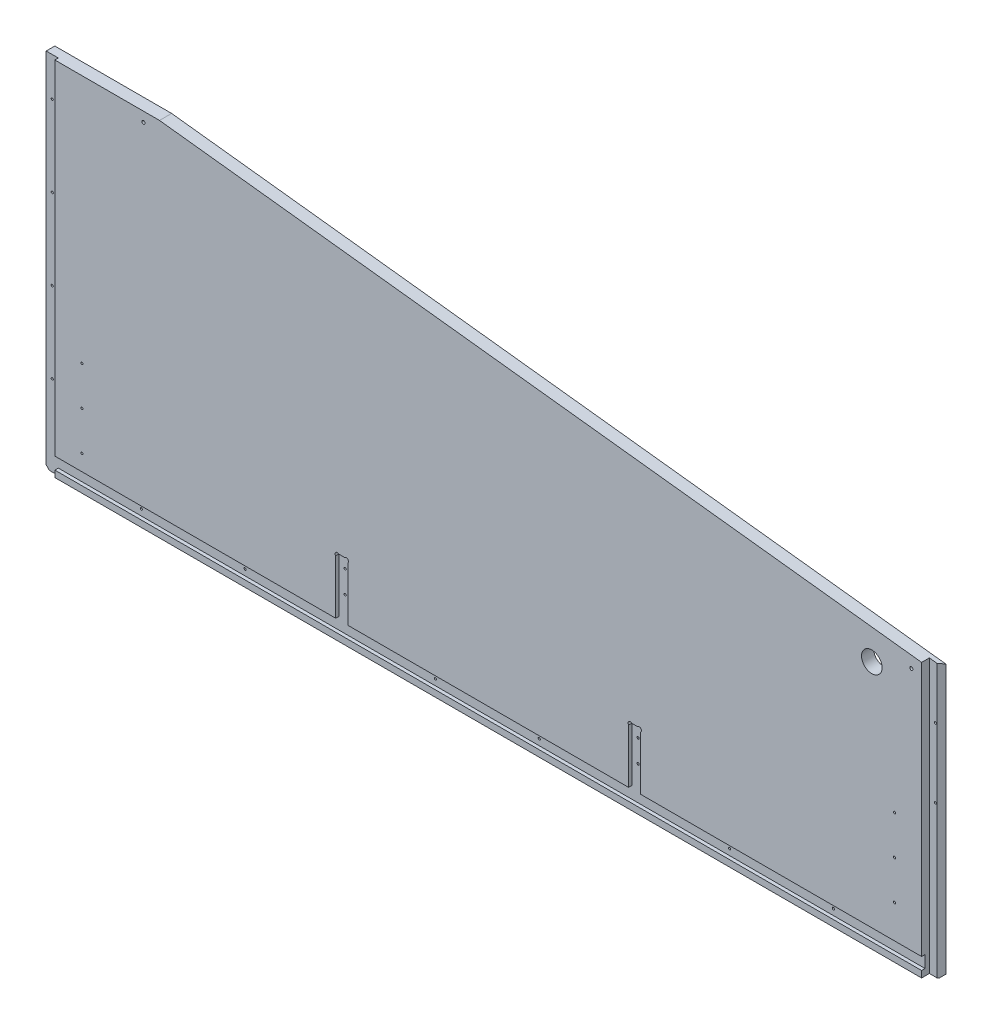
SolidWorks part; units mm, degrees
material "Pine"
ref_plane "Front Plane" through (0, 0, 0) normal (0, 0, 1) x (1, 0, 0)
ref_plane "Top Plane" through (0, 0, 0) normal (0, 1, 0) x (1, 0, 0)
ref_plane "Right Plane" through (0, 0, 0) normal (1, 0, 0) x (0, 0, -1)
sketch "Sketch1" plane through (0, 0, 0) normal (0, 0, 1) x (1, 0, 0)
  line L0 (8932.6508, -5243.5125) -> (10226.1458, -5243.5125)
  line L1 (9086.3208, -4722.0918) -> (10222.9708, -4853.7812)
  line L2 (8914.8708, -6342.0625) -> (10197.5708, -6342.0625)
  line L3 (8914.8708, -5808.6625) -> (10197.5708, -5808.6625)
  line L4 (8919.6333, -5253.0375) -> (10218.2083, -5253.0375)
  line L5 (9134.2633, -4656.1375) -> (9134.2633, -4638.3575)
  line L6 (9091.0833, -4638.3575) -> (9134.2633, -4638.3575)
  line L7 (9091.0833, -4567.2375) -> (9091.0833, -4638.3575)
  line L8 (9134.2633, -4656.1375) -> (9581.3033, -4656.1375)
  line L9 (9091.0833, -4567.2375) -> (9624.4833, -4567.2375)
  line L10 (9581.3033, -4656.1375) -> (9581.3033, -4638.3575)
  line L11 (9581.3033, -4638.3575) -> (9624.4833, -4638.3575)
  line L12 (9624.4833, -4567.2375) -> (9624.4833, -4638.3575)
  line L13 (8932.6508, -5225.7325) -> (9344.9775, -5225.7325)
  line L14 (8932.6508, -5256.2125) -> (8932.6508, -5243.5125)
  line L15 (8911.6958, -5256.2125) -> (8932.6508, -5256.2125)
  line L16 (8914.8708, -4722.0918) -> (9086.3208, -4722.0918)
  line L17 (8911.6958, -4715.5913) -> (8932.6508, -4715.5913)
  line L18 (8914.8708, -6342.0625) -> (8914.8708, -5808.6625)
  line L19 (12082.9917, -4722.0918) -> (10946.3417, -4853.7812)
  line L20 (12236.6617, -5243.5125) -> (10943.1667, -5243.5125)
  line L21 (10951.1042, -5253.0375) -> (12249.6792, -5253.0375)
  line L22 (10838.3917, -5656.2625) -> (11308.2917, -5656.2625)
  line L23 (10838.3917, -5719.7625) -> (11308.2917, -5719.7625)
  line L24 (10838.3917, -5742.5368) -> (11308.2917, -5742.5368)
  line L25 (10806.6417, -6342.0625) -> (11340.0417, -6342.0625)
  line L26 (10803.4667, -6335.7125) -> (11343.2167, -6335.7125)
  line L27 (10803.4667, -6317.9325) -> (11343.2167, -6317.9325)
  line L28 (10943.1667, -5225.7325) -> (11376.4483, -5225.7325)
  line L29 (11506.7292, -4754.5625) -> (10806.6417, -4827.5875)
  line L30 (11506.7292, -4567.2375) -> (11506.7292, -4754.5625)
  line L31 (10806.6417, -4567.2375) -> (10806.6417, -4827.5875)
  line L32 (10806.6417, -4567.2375) -> (11506.7292, -4567.2375)
  line L33 (10235.6708, -6329.3625) -> (10245.1958, -6329.3625)
  line L34 (10245.1958, -6329.3625) -> (10254.7208, -6278.5625)
  line L35 (10302.3458, -6329.3625) -> (10311.8708, -6278.5625)
  line L36 (10302.3458, -6329.3625) -> (10292.8208, -6329.3625)
  line L37 (10245.1958, -5821.3625) -> (10254.7208, -5872.1625)
  line L38 (10235.6708, -5821.3625) -> (10245.1958, -5821.3625)
  line L39 (10292.8208, -5821.3625) -> (10302.3458, -5821.3625)
  line L40 (10302.3458, -5821.3625) -> (10311.8708, -5872.1625)
  line L41 (10235.6708, -5821.3625) -> (10235.6708, -6329.3625)
  line L42 (10254.7208, -5872.1625) -> (10254.7208, -6278.5625)
  line L43 (10311.8708, -5872.1625) -> (10311.8708, -6278.5625)
  line L44 (10292.8208, -5821.3625) -> (10292.8208, -6329.3625)
  line L45 (8932.6508, -5225.7325) -> (8932.6508, -4715.5913)
  line L46 (8911.6958, -4715.5913) -> (8911.6958, -5256.2125)
  line L47 (8914.8708, -5248.275) -> (8914.8708, -4722.0918)
  line L48 (8919.6333, -5253.0375) -> (8914.8708, -5248.275)
  line L49 (8914.8708, -5145.0875) -> (8937.426, -5145.0875)
  line L50 (8914.8708, -5202.2375) -> (8937.426, -5202.2375)
  line L51 (10838.3917, -5656.2625) -> (10838.3917, -5719.7625)
  line L52 (10832.0417, -5736.1868) -> (10856.1717, -5736.1868)
  line L53 (10806.6417, -6342.0625) -> (10806.6417, -5818.7368)
  line L54 (10832.0417, -5649.9125) -> (10856.1717, -5649.9125)
  line L55 (10832.0417, -5726.1125) -> (10856.1717, -5726.1125)
  line L56 (10806.6417, -5818.7368) -> (10833.9015, -5818.7368)
  line L57 (10832.0417, -5806.0442) -> (10851.6815, -5806.0442)
  line L58 (10856.1717, -5801.5541) -> (10856.1717, -5736.1868)
  line L59 (10838.3917, -5814.2467) -> (10838.3917, -5742.5368)
  line L60 (10832.0417, -5806.0442) -> (10832.0417, -5736.1868)
  line L61 (10803.4667, -6317.9325) -> (10803.4667, -6335.7125)
  line L62 (10197.5708, -5808.6625) -> (10197.5708, -6342.0625)
  line L63 (9762.3842, -6348.4125) -> (9762.3842, -5802.3125)
  line L64 (9780.1642, -6348.4125) -> (9762.3842, -6348.4125)
  line L65 (9780.1642, -5802.3125) -> (9780.1642, -6348.4125)
  line L66 (9762.3842, -5802.3125) -> (9780.1642, -5802.3125)
  line L67 (9332.2775, -6348.4125) -> (9332.2775, -5802.3125)
  line L68 (9332.2775, -6348.4125) -> (9350.0575, -6348.4125)
  line L69 (9350.0575, -5802.3125) -> (9350.0575, -6348.4125)
  line L70 (9332.2775, -5802.3125) -> (9350.0575, -5802.3125)
  line L71 (9993.8374, -6061.075) -> (9993.8374, -6045.2418)
  line L72 (9998.5999, -6065.8375) -> (10014.4331, -6065.8375)
  line L73 (9998.5999, -6084.8875) -> (10014.4331, -6084.8875)
  line L74 (9993.8374, -6105.4832) -> (9993.8374, -6089.65)
  line L75 (9974.7874, -6105.4832) -> (9974.7874, -6089.65)
  line L76 (9954.1917, -6084.8875) -> (9970.0249, -6084.8875)
  line L77 (9974.7874, -6061.075) -> (9974.7874, -6045.2418)
  line L78 (9954.1917, -6065.8375) -> (9970.0249, -6065.8375)
  line L79 (10793.9417, -6237.2875) -> (10816.4969, -6237.2875)
  line L80 (10793.9417, -6294.4375) -> (10816.4969, -6294.4375)
  line L81 (10856.1717, -5649.9125) -> (10856.1717, -5726.1125)
  line L82 (10832.0417, -5726.1125) -> (10832.0417, -5649.9125)
  line L83 (10226.1458, -5225.7325) -> (10226.1458, -5243.5125)
  line L84 (10205.1908, -5257.8) -> (10205.1908, -4844.2499)
  line L85 (10230.9083, -4844.2499) -> (10230.9083, -5257.8)
  line L86 (10205.1908, -5257.8) -> (10230.9083, -5257.8)
  line L87 (10205.1908, -4844.2499) -> (10230.9083, -4844.2499)
  line L88 (10946.3417, -5176.8375) -> (10968.8969, -5176.8375)
  line L89 (9349.4676, -5141.9125) -> (9358.2674, -5141.9125)
  line L90 (10946.3417, -5119.6875) -> (10968.8969, -5119.6875)
  line L91 (9929.011, -4660.9635) -> (10066.0807, -4660.9635)
  line L92 (9929.011, -4678.7435) -> (10066.0807, -4678.7435)
  line L93 (10943.1667, -5225.7325) -> (10943.1667, -5243.5125)
  line L94 (10946.3417, -5248.275) -> (10951.1042, -5253.0375)
  line L95 (10946.3417, -5257.8063) -> (10946.3417, -4849.0188)
  line L96 (10964.1217, -5257.8) -> (10964.1217, -4844.2499)
  line L97 (10938.4042, -4844.2499) -> (10938.4042, -5257.8)
  line L98 (10938.4042, -5257.8) -> (10964.1217, -5257.8)
  line L99 (10964.1217, -4844.2499) -> (10938.4042, -4844.2499)
  line L100 (10344.8908, -4560.8875) -> (10369.0208, -4560.8875)
  line L101 (10344.8908, -4560.8875) -> (10369.0208, -4560.8875)
  line L102 (10800.2917, -4560.8875) -> (10824.4217, -4560.8875)
  line L103 (10200.4156, -5119.6875) -> (10222.9708, -5119.6875)
  line L104 (10200.4156, -5176.8375) -> (10222.9708, -5176.8375)
  line L105 (9344.9775, -5146.4026) -> (9344.9775, -5225.7325)
  line L106 (10344.8908, -4560.8875) -> (10344.8908, -4833.9375)
  line L107 (9792.8642, -5225.7325) -> (9792.8642, -5146.4026)
  line L108 (9362.7575, -5225.7325) -> (9775.0842, -5225.7325)
  line L109 (9680.3633, -4761.8396) -> (9680.3633, -4559.9604)
  line L110 (9656.2333, -4559.9604) -> (9680.3633, -4559.9604)
  line L111 (9656.2333, -4761.8396) -> (9680.3633, -4761.8396)
  line L112 (9656.2333, -4761.8396) -> (9656.2333, -4559.9604)
  line L113 (9779.5743, -5141.9125) -> (9788.374, -5141.9125)
  line L114 (10070.5708, -4665.4536) -> (10070.5708, -4674.2534)
  line L115 (9924.5208, -4674.2534) -> (9924.5208, -4665.4536)
  line L116 (12127.4417, -6188.3925) -> (12205.5015, -6188.3925)
  line L117 (12209.9917, -6170.6125) -> (12209.9917, -6183.9024)
  line L118 (9792.8642, -5225.7325) -> (10226.1458, -5225.7325)
  line L119 (9662.5833, -4754.5625) -> (10362.6708, -4827.5875)
  line L120 (9662.5833, -4567.2375) -> (9662.5833, -4754.5625)
  line L121 (10362.6708, -4567.2375) -> (10362.6708, -4827.5875)
  line L122 (9662.5833, -4567.2375) -> (10362.6708, -4567.2375)
  line L123 (10824.4217, -4833.9375) -> (10800.2917, -4833.9375)
  line L124 (10800.2917, -4833.9375) -> (10800.2917, -4560.8875)
  line L125 (10824.4217, -4560.8875) -> (10824.4217, -4833.9375)
  line L126 (10344.8908, -4833.9375) -> (10369.0208, -4833.9375)
  line L127 (10369.0208, -4833.9375) -> (10369.0208, -4560.8875)
  line L128 (10222.9708, -5248.275) -> (10218.2083, -5253.0375)
  line L129 (10222.9708, -5257.8063) -> (10222.9708, -4849.0188)
  line L130 (11734.6544, -5701.375) -> (11739.2301, -5701.375)
  line L131 (9362.7575, -5225.7325) -> (9362.7575, -5146.4026)
  line L132 (9775.0842, -5146.4026) -> (9775.0842, -5225.7325)
  line L133 (11761.3864, -5701.375) -> (11756.8282, -5701.375)
  line L134 (11734.6544, -5693.755) -> (11739.2301, -5693.755)
  line L135 (11761.4039, -5693.755) -> (11756.8282, -5693.755)
  line L136 (11734.6544, -5701.375) -> (11739.2301, -5701.375)
  line L137 (11744.3462, -5721.3024) -> (11744.3462, -5706.4179)
  line L138 (11751.7122, -5721.3024) -> (11751.7122, -5706.4179)
  line L139 (11740.0917, -6170.6125) -> (11740.0917, -6183.9024)
  line L140 (11689.2917, -6188.3925) -> (11822.6417, -6188.3925)
  line L141 (11689.2917, -6348.4093) -> (11689.2917, -6164.2657)
  line L142 (11689.2917, -6164.2657) -> (11746.4417, -6164.2657)
  line L143 (11746.4417, -6164.2657) -> (11746.4417, -6188.3925)
  line L144 (11689.2917, -6164.2657) -> (11746.4417, -6164.2657)
  line L145 (11340.0417, -5818.7368) -> (11340.0417, -6342.0625)
  line L146 (11290.5117, -5726.1125) -> (11314.6417, -5726.1125)
  line L147 (11290.5117, -5649.9125) -> (11290.5117, -5726.1125)
  line L148 (11340.0417, -5818.7368) -> (11312.7818, -5818.7368)
  line L149 (11314.6417, -5806.0442) -> (11295.0018, -5806.0442)
  line L150 (11290.5117, -5801.5541) -> (11290.5117, -5736.1868)
  line L151 (11308.2917, -5814.2467) -> (11308.2917, -5742.5368)
  line L152 (11314.6417, -5806.0442) -> (11314.6417, -5736.1868)
  line L153 (11290.5117, -5736.1868) -> (11314.6417, -5736.1868)
  line L154 (11848.0417, -6267.1325) -> (11962.3417, -6267.1325)
  line L155 (11962.3417, -6267.1325) -> (11962.3417, -6203.6325)
  line L156 (11343.2167, -6317.9325) -> (11343.2167, -6335.7125)
  line L157 (11365.4417, -5656.2625) -> (11365.4417, -5719.7625)
  line L158 (11365.4417, -5656.2625) -> (11479.7417, -5656.2625)
  line L159 (11778.1917, -6071.3937) -> (11802.3217, -6071.3937)
  line L160 (11314.6417, -5726.1125) -> (11314.6417, -5649.9125)
  line L161 (11314.6417, -5649.9125) -> (11290.5117, -5649.9125)
  line L162 (11308.2917, -5719.7625) -> (11308.2917, -5656.2625)
  line L163 (11689.2917, -6348.4093) -> (11713.4217, -6348.4093)
  line L164 (12203.6417, -6164.2657) -> (12260.7917, -6164.2657)
  line L165 (11713.4217, -6348.4093) -> (11713.4217, -6164.2657)
  line L166 (11695.6417, -6342.0625) -> (11695.6417, -6170.6125)
  line L167 (11695.6417, -6048.5337) -> (11699.4517, -6052.3437)
  line L168 (11822.6417, -6292.5325) -> (11822.6417, -6188.3925)
  line L169 (11695.6417, -6342.0625) -> (11695.6417, -6170.6125)
  line L170 (11848.0417, -6203.6325) -> (11962.3417, -6203.6325)
  line L171 (11848.0417, -6203.6325) -> (11848.0417, -6267.1325)
  line L172 (11987.7417, -6267.1325) -> (11987.7417, -6203.6325)
  line L173 (11784.5417, -6077.7437) -> (11784.5417, -6141.2438)
  line L174 (11517.8417, -5656.2625) -> (11632.1417, -5656.2625)
  line L175 (11632.1417, -5656.2625) -> (11632.1417, -5719.7625)
  line L176 (11632.1417, -5719.7625) -> (11517.8417, -5719.7625)
  line L177 (11517.8417, -5719.7625) -> (11517.8417, -5656.2625)
  line L178 (11692.4667, -6028.2137) -> (11692.4667, -6045.9937)
  line L179 (11695.6417, -5979.3188) -> (11718.1969, -5979.3188)
  line L180 (11695.6417, -5922.1687) -> (11718.1969, -5922.1687)
  line L181 (11821.0415, -5722.9375) -> (11821.0415, -5943.6)
  line L182 (11687.7042, -5651.5) -> (11701.9917, -5651.5)
  line L183 (11687.7042, -5651.5) -> (11687.7042, -6055.5251)
  line L184 (11687.7042, -6055.5251) -> (11701.9917, -6055.5251)
  line L185 (11701.9917, -6055.5251) -> (11701.9917, -5651.5)
  line L186 (11695.6417, -6055.2013) -> (11695.6417, -5649.595)
  line L187 (11695.6417, -5656.2625) -> (11695.6417, -6048.5337)
  line L188 (11695.6417, -6170.6125) -> (11740.0917, -6170.6125)
  line L189 (12203.6417, -6164.2657) -> (12203.6417, -6188.3925)
  line L190 (12254.4417, -6342.0625) -> (12254.4417, -6170.6125)
  line L191 (12129.0419, -5943.6) -> (12129.0419, -5722.9375)
  line L192 (12254.4417, -6048.5337) -> (12250.6317, -6052.3437)
  line L193 (12257.6167, -6045.9937) -> (12257.6167, -6028.2137)
  line L194 (12248.0917, -5651.5) -> (12262.3792, -5651.5)
  line L195 (12262.3792, -5651.5) -> (12262.3792, -6055.5251)
  line L196 (12262.3792, -6055.5251) -> (12248.0917, -6055.5251)
  line L197 (12248.0917, -6055.5251) -> (12248.0917, -5651.5)
  line L198 (12254.4417, -6141.2438) -> (12254.4417, -6077.7437)
  line L199 (12236.6617, -6164.2657) -> (12260.7917, -6164.2657)
  line L200 (12102.0417, -6267.1325) -> (11987.7417, -6267.1325)
  line L201 (11330.1865, -6237.2875) -> (11352.7417, -6237.2875)
  line L202 (11330.1865, -6294.4375) -> (11352.7417, -6294.4375)
  line L203 (11474.6617, -5851.8425) -> (11492.4417, -5851.8425)
  line L204 (11474.6617, -5808.6625) -> (11474.6617, -5851.8425)
  line L205 (11403.5417, -5808.6625) -> (11474.6617, -5808.6625)
  line L206 (11492.4417, -5851.8425) -> (11492.4417, -6298.8825)
  line L207 (11403.5417, -6342.0625) -> (11403.5417, -5808.6625)
  line L208 (11474.6617, -6298.8825) -> (11492.4417, -6298.8825)
  line L209 (11474.6617, -6342.0625) -> (11474.6617, -6298.8825)
  line L210 (11403.5417, -6342.0625) -> (11474.6617, -6342.0625)
  line L211 (11619.4417, -5851.8425) -> (11601.6617, -5851.8425)
  line L212 (11601.6617, -5808.6625) -> (11601.6617, -5851.8425)
  line L213 (11530.5417, -5808.6625) -> (11601.6617, -5808.6625)
  line L214 (11619.4417, -5851.8425) -> (11619.4417, -6298.8825)
  line L215 (11530.5417, -6342.0625) -> (11530.5417, -5808.6625)
  line L216 (11619.4417, -6298.8825) -> (11601.6617, -6298.8825)
  line L217 (11601.6617, -6342.0625) -> (11601.6617, -6298.8825)
  line L218 (11530.5417, -6342.0625) -> (11601.6617, -6342.0625)
  line L219 (11479.7417, -5719.7625) -> (11479.7417, -5656.2625)
  line L220 (11365.4417, -5719.7625) -> (11479.7417, -5719.7625)
  line L221 (11778.1917, -6147.5937) -> (11802.3217, -6147.5937)
  line L222 (11802.3217, -6071.3937) -> (11802.3217, -6147.5937)
  line L223 (11778.1917, -6147.5937) -> (11778.1917, -6071.3937)
  line L224 (12254.4417, -5922.1687) -> (12231.8865, -5922.1687)
  line L225 (12254.4417, -5979.3188) -> (12231.8865, -5979.3188)
  line L226 (12254.4417, -6055.2013) -> (12254.4417, -5649.595)
  line L227 (12254.4417, -6048.5337) -> (12254.4417, -5656.2625)
  line L228 (11841.6917, -5702.2873) -> (12108.3917, -5702.2873)
  line L229 (11822.6417, -6292.5325) -> (12127.4417, -6292.5325)
  line L230 (12127.4417, -6292.5325) -> (12127.4417, -6188.3925)
  line L231 (12254.4417, -6170.6125) -> (12209.9917, -6170.6125)
  line L232 (11695.6417, -6342.0625) -> (12254.4417, -6342.0625)
  line L233 (12236.6617, -6348.4093) -> (12260.7917, -6348.4093)
  line L234 (12260.7917, -6348.4093) -> (12260.7917, -6164.2657)
  line L235 (12236.6617, -6348.4093) -> (12236.6617, -6164.2657)
  line L236 (12102.0417, -6203.6325) -> (12102.0417, -6267.1325)
  line L237 (11987.7417, -6203.6325) -> (12102.0417, -6203.6325)
  line L238 (12236.6617, -6147.5937) -> (12236.6617, -6071.3937)
  line L239 (12203.6417, -6188.3925) -> (12260.7917, -6188.3925)
  line L240 (11098.7417, -4665.4536) -> (11098.7417, -4674.2534)
  line L241 (11394.2283, -5146.4026) -> (11394.2283, -5225.7325)
  line L242 (11376.4483, -5225.7325) -> (11376.4483, -5146.4026)
  line L243 (11394.2283, -5225.7325) -> (11806.555, -5225.7325)
  line L244 (11841.6917, -5964.2502) -> (12108.3917, -5964.2502)
  line L245 (12236.6617, -6147.5937) -> (12260.7917, -6147.5937)
  line L246 (12236.6617, -5256.2125) -> (12236.6617, -5243.5125)
  line L247 (12260.7917, -6147.5937) -> (12260.7917, -6071.3937)
  line L248 (12260.7917, -6071.3937) -> (12236.6617, -6071.3937)
  line L249 (12254.4417, -6077.7437) -> (11784.5417, -6077.7437)
  line L250 (11784.5417, -6141.2438) -> (12254.4417, -6141.2438)
  line L252 (12254.4417, -5656.2625) -> (11695.6417, -5656.2625)
  line L253 (11699.4517, -6052.3437) -> (12250.6317, -6052.3437)
  line L254 (11692.4667, -6045.9937) -> (12257.6167, -6045.9937)
  line L255 (11692.4667, -6028.2137) -> (12257.6167, -6028.2137)
  line L256 (11824.335, -5146.4026) -> (11824.335, -5225.7325)
  line L257 (11811.0451, -5141.9125) -> (11819.8449, -5141.9125)
  line L258 (11244.7917, -4674.2534) -> (11244.7917, -4665.4536)
  line L259 (11806.555, -5225.7325) -> (11806.555, -5146.4026)
  line L260 (11488.9492, -4761.8396) -> (11488.9492, -4559.9604)
  line L261 (11488.9492, -4559.9604) -> (11513.0792, -4559.9604)
  line L262 (11488.9492, -4761.8396) -> (11513.0792, -4761.8396)
  line L263 (11513.0792, -4761.8396) -> (11513.0792, -4559.9604)
  line L264 (11240.3015, -4660.9635) -> (11103.2318, -4660.9635)
  line L265 (11103.2318, -4678.7435) -> (11240.3015, -4678.7435)
  line L266 (12236.6617, -5225.7325) -> (12236.6617, -4715.5913)
  line L267 (12257.6167, -4715.5913) -> (12257.6167, -5256.2125)
  line L268 (12254.4417, -5248.275) -> (12254.4417, -4722.0918)
  line L269 (12236.6617, -5225.7325) -> (11824.335, -5225.7325)
  line L270 (12035.0492, -4656.1375) -> (12035.0492, -4638.3575)
  line L271 (12078.2292, -4638.3575) -> (12035.0492, -4638.3575)
  line L272 (12078.2292, -4567.2375) -> (12078.2292, -4638.3575)
  line L273 (12035.0492, -4656.1375) -> (11588.0092, -4656.1375)
  line L274 (11544.8292, -4567.2375) -> (12078.2292, -4567.2375)
  line L275 (11588.0092, -4656.1375) -> (11588.0092, -4638.3575)
  line L276 (11544.8292, -4638.3575) -> (11588.0092, -4638.3575)
  line L277 (11544.8292, -4567.2375) -> (11544.8292, -4638.3575)
  line L278 (12249.6792, -5253.0375) -> (12254.4417, -5248.275)
  line L280 (12257.6167, -5256.2125) -> (12236.6617, -5256.2125)
  line L281 (12231.8865, -5145.0875) -> (12254.4417, -5145.0875)
  line L282 (12231.8865, -5202.2375) -> (12254.4417, -5202.2375)
  line L283 (12236.6617, -4715.5913) -> (12257.6167, -4715.5913)
  line L284 (12082.9917, -4722.0918) -> (12254.4417, -4722.0918)
  line L285 (11380.9385, -5141.9125) -> (11389.7382, -5141.9125)
  circle A0 centre (8923.7608, -4778.9042) radius 1.5875
  circle A1 centre (9062.6598, -4736.3765) radius 2.3685
  circle A2 centre (9051.3958, -6281.7375) radius 22.225
  circle A3 centre (9083.1458, -6249.9875) radius 1.5875
  circle A4 centre (9083.1458, -6313.4875) radius 1.5875
  circle A5 centre (9019.6458, -6249.9875) radius 1.5875
  circle A6 centre (9019.6458, -6313.4875) radius 1.5875
  circle A7 centre (8972.3383, -5202.2375) radius 1.5875
  circle A8 centre (8923.7608, -5015.9708) radius 1.5875
  circle A9 centre (8923.7608, -5134.5042) radius 1.5875
  circle A10 centre (9054.5708, -5234.6225) radius 1.5875
  circle A11 centre (8923.7608, -4897.4375) radius 1.5875
  circle A12 centre (8972.3383, -5087.9375) radius 1.5875
  circle A13 centre (8972.3383, -5145.0875) radius 1.5875
  circle A14 centre (10847.2817, -5668.9625) radius 1.5875
  circle A15 centre (10847.2817, -5707.0625) radius 1.5875
  circle A16 centre (10847.2817, -5755.2368) radius 1.5875
  circle A17 centre (10851.4092, -6237.2875) radius 1.5875
  circle A18 centre (10851.4092, -6294.4375) radius 1.5875
  circle A19 centre (10847.2817, -5793.3442) radius 1.5875
  arc A20 (10833.9015, -5818.7368) -> (10838.3917, -5814.2467) centre (10836.1466, -5816.4918) ccw
  arc A21 (10851.6815, -5806.0442) -> (10856.1717, -5801.5541) centre (10853.9266, -5803.7992) ccw
  circle A22 centre (10882.8417, -6040.4375) radius 1.5875
  circle A23 centre (10882.8417, -6218.2375) radius 1.5875
  circle A24 centre (10882.8417, -5862.6375) radius 1.5875
  circle A25 centre (10908.2417, -6326.8225) radius 1.5875
  circle A26 centre (10908.2417, -6326.8225) radius 1.5875
  circle A27 centre (10851.4092, -6180.1375) radius 1.5875
  circle A28 centre (10815.5317, -4783.4231) radius 1.5875
  circle A29 centre (10815.5317, -4696.9488) radius 1.5875
  circle A30 centre (10815.5317, -4610.4746) radius 1.5875
  circle A31 centre (10979.1323, -4867.0082) radius 2.3685
  circle A32 centre (10190.1802, -4867.0082) radius 2.3685
  circle A33 centre (10955.2317, -4929.9812) radius 1.5875
  circle A34 centre (10955.2317, -5031.5812) radius 1.5875
  circle A35 centre (10214.0808, -4929.9812) radius 1.5875
  circle A36 centre (10214.0808, -5031.5812) radius 1.5875
  circle A37 centre (9341.1675, -6265.8625) radius 1.5875
  circle A38 centre (9771.2742, -5884.8625) radius 1.5875
  circle A39 centre (9771.2742, -6138.8625) radius 1.5875
  circle A40 centre (9771.2742, -6011.8625) radius 1.5875
  arc A41 (10036.2287, -6113.8083) -> (10051.3426, -6111.6033) centre (10042.9639, -6107.0732) ccw
  arc A42 (10051.3426, -6111.6033) -> (10051.3426, -6039.1217) centre (9984.3124, -6075.3625) ccw
  arc A43 (10051.3426, -6039.1217) -> (10036.2287, -6036.9167) centre (10042.9639, -6043.6518) ccw
  arc A44 (10034.5851, -6102.5431) -> (10034.5851, -6048.1819) centre (9984.3124, -6075.3625) ccw
  arc A45 (10034.5851, -6102.5431) -> (10036.2287, -6113.8083) centre (10042.9639, -6107.0732) ccw
  arc A46 (10036.2287, -6036.9167) -> (10034.5851, -6048.1819) centre (10042.9639, -6043.6518) ccw
  arc A47 (9945.8666, -6127.2787) -> (9948.0717, -6142.3927) centre (9952.6018, -6134.0139) ccw
  arc A48 (9948.0717, -6142.3927) -> (10020.5532, -6142.3927) centre (9984.3124, -6075.3625) ccw
  arc A49 (10020.5532, -6142.3927) -> (10022.7583, -6127.2787) centre (10016.0231, -6134.0139) ccw
  arc A50 (9957.1319, -6125.6352) -> (10011.493, -6125.6352) centre (9984.3124, -6075.3625) ccw
  arc A51 (9957.1319, -6125.6352) -> (9945.8666, -6127.2787) centre (9952.6018, -6134.0139) ccw
  arc A52 (10022.7583, -6127.2787) -> (10011.493, -6125.6352) centre (10016.0231, -6134.0139) ccw
  arc A53 (9932.3962, -6036.9167) -> (9917.2822, -6039.1217) centre (9925.661, -6043.6518) ccw
  arc A54 (9917.2822, -6039.1217) -> (9917.2822, -6111.6033) centre (9984.3124, -6075.3625) ccw
  arc A55 (9917.2822, -6111.6033) -> (9932.3962, -6113.8083) centre (9925.661, -6107.0732) ccw
  arc A56 (9934.0398, -6048.1819) -> (9934.0398, -6102.5431) centre (9984.3124, -6075.3625) ccw
  arc A57 (9934.0398, -6048.1819) -> (9932.3962, -6036.9167) centre (9925.661, -6043.6518) ccw
  arc A58 (9932.3962, -6113.8083) -> (9934.0398, -6102.5431) centre (9925.661, -6107.0732) ccw
  arc A59 (9945.8666, -6023.4463) -> (9957.1319, -6025.0898) centre (9952.6018, -6016.7111) ccw
  arc A60 (10011.493, -6025.0898) -> (10022.7583, -6023.4463) centre (10016.0231, -6016.7111) ccw
  arc A61 (10011.493, -6025.0898) -> (9957.1319, -6025.0898) centre (9984.3124, -6075.3625) ccw
  arc A62 (9948.0717, -6008.3323) -> (9945.8666, -6023.4463) centre (9952.6018, -6016.7111) ccw
  arc A63 (10020.5532, -6008.3323) -> (9948.0717, -6008.3323) centre (9984.3124, -6075.3625) ccw
  arc A64 (10022.7583, -6023.4463) -> (10020.5532, -6008.3323) centre (10016.0231, -6016.7111) ccw
  arc A65 (10005.0943, -6187.7574) -> (10096.7073, -6096.1443) centre (9984.3124, -6075.3625) ccw
  arc A66 (9993.8374, -6178.3911) -> (10005.0943, -6187.7574) centre (10003.3624, -6178.3911) ccw
  arc A67 (10001.6306, -6169.0249) -> (10077.9748, -6092.6807) centre (9984.3124, -6075.3625) ccw
  arc A68 (10087.3411, -6084.8875) -> (10077.9748, -6092.6807) centre (10087.3411, -6094.4125) ccw
  arc A69 (10001.6306, -6169.0249) -> (9993.8374, -6178.3911) centre (10003.3624, -6178.3911) ccw
  arc A70 (9963.5306, -6187.7574) -> (9974.7874, -6178.3911) centre (9965.2624, -6178.3911) ccw
  arc A71 (9871.9176, -6096.1443) -> (9963.5306, -6187.7574) centre (9984.3124, -6075.3625) ccw
  arc A72 (9881.2838, -6084.8875) -> (9871.9176, -6096.1443) centre (9881.2838, -6094.4125) ccw
  arc A73 (9890.65, -6092.6807) -> (9966.9943, -6169.0249) centre (9984.3124, -6075.3625) ccw
  arc A74 (9974.7874, -6178.3911) -> (9966.9943, -6169.0249) centre (9965.2624, -6178.3911) ccw
  arc A75 (9890.65, -6092.6807) -> (9881.2838, -6084.8875) centre (9881.2838, -6094.4125) ccw
  arc A76 (9871.9176, -6054.5807) -> (9881.2838, -6065.8375) centre (9881.2838, -6056.3125) ccw
  arc A77 (9963.5306, -5962.9676) -> (9871.9176, -6054.5807) centre (9984.3124, -6075.3625) ccw
  arc A78 (9974.7874, -5972.3339) -> (9963.5306, -5962.9676) centre (9965.2624, -5972.3339) ccw
  arc A79 (9966.9943, -5981.7001) -> (9890.65, -6058.0443) centre (9984.3124, -6075.3625) ccw
  arc A80 (9881.2838, -6065.8375) -> (9890.65, -6058.0443) centre (9881.2838, -6056.3125) ccw
  arc A81 (9966.9943, -5981.7001) -> (9974.7874, -5972.3339) centre (9965.2624, -5972.3339) ccw
  arc A82 (10077.9748, -6058.0443) -> (10087.3411, -6065.8375) centre (10087.3411, -6056.3125) ccw
  arc A83 (9993.8374, -5972.3339) -> (10001.6306, -5981.7001) centre (10003.3624, -5972.3339) ccw
  arc A84 (10077.9748, -6058.0443) -> (10001.6306, -5981.7001) centre (9984.3124, -6075.3625) ccw
  arc A85 (10087.3411, -6065.8375) -> (10096.7073, -6054.5807) centre (10087.3411, -6056.3125) ccw
  arc A86 (10096.7073, -6054.5807) -> (10005.0943, -5962.9676) centre (9984.3124, -6075.3625) ccw
  arc A87 (10005.0943, -5962.9676) -> (9993.8374, -5972.3339) centre (10003.3624, -5972.3339) ccw
  arc A88 (10014.4331, -6065.8375) -> (10018.7361, -6059.0339) centre (10014.4331, -6061.075) ccw
  arc A89 (10018.7361, -6059.0339) -> (10000.641, -6040.9388) centre (9984.3124, -6075.3625) ccw
  arc A90 (10000.641, -6040.9388) -> (9993.8374, -6045.2418) centre (9998.5999, -6045.2418) ccw
  arc A91 (9993.8374, -6061.075) -> (9998.5999, -6065.8375) centre (9998.5999, -6061.075) ccw
  arc A92 (9993.8374, -6105.4832) -> (10000.641, -6109.7862) centre (9998.5999, -6105.4832) ccw
  arc A93 (10000.641, -6109.7862) -> (10018.7361, -6091.6911) centre (9984.3124, -6075.3625) ccw
  arc A94 (10018.7361, -6091.6911) -> (10014.4331, -6084.8875) centre (10014.4331, -6089.65) ccw
  arc A95 (9998.5999, -6084.8875) -> (9993.8374, -6089.65) centre (9998.5999, -6089.65) ccw
  arc A96 (9954.1917, -6084.8875) -> (9949.8888, -6091.6911) centre (9954.1917, -6089.65) ccw
  arc A97 (9949.8888, -6091.6911) -> (9967.9839, -6109.7862) centre (9984.3124, -6075.3625) ccw
  arc A98 (9967.9839, -6109.7862) -> (9974.7874, -6105.4832) centre (9970.0249, -6105.4832) ccw
  arc A99 (9974.7874, -6089.65) -> (9970.0249, -6084.8875) centre (9970.0249, -6089.65) ccw
  arc A100 (9970.0249, -6065.8375) -> (9974.7874, -6061.075) centre (9970.0249, -6061.075) ccw
  arc A101 (9949.8888, -6059.0339) -> (9954.1917, -6065.8375) centre (9954.1917, -6061.075) ccw
  arc A102 (9967.9839, -6040.9388) -> (9949.8888, -6059.0339) centre (9984.3124, -6075.3625) ccw
  arc A103 (9974.7874, -6045.2418) -> (9967.9839, -6040.9388) centre (9970.0249, -6045.2418) ccw
  arc A104 (10096.7073, -6096.1443) -> (10087.3411, -6084.8875) centre (10087.3411, -6094.4125) ccw
  circle A105 centre (9771.2742, -6265.8625) radius 1.5875
  circle A106 centre (9341.1675, -5884.8625) radius 1.5875
  circle A107 centre (9341.1675, -6138.8625) radius 1.5875
  circle A108 centre (9341.1675, -6011.8625) radius 1.5875
  circle A109 centre (11037.2315, -4887.5494) radius 15.0812
  arc A110 (9349.4676, -5141.9125) -> (9344.9775, -5146.4026) centre (9347.2226, -5144.1576) ccw
  arc A111 (9362.7575, -5146.4026) -> (9358.2674, -5141.9125) centre (9360.5124, -5144.1576) ccw
  circle A112 centre (9946.7458, -4669.8535) radius 1.5875
  arc A113 (9924.5208, -4674.2534) -> (9929.011, -4678.7435) centre (9926.7659, -4676.4984) ccw
  circle A114 centre (11003.8092, -5176.8375) radius 1.5875
  circle A115 centre (11003.8092, -5119.6875) radius 1.5875
  circle A116 centre (10353.7808, -4696.9488) radius 1.5875
  circle A117 centre (10353.7808, -4610.4746) radius 1.5875
  circle A118 centre (10353.7808, -4783.4231) radius 1.5875
  circle A119 centre (11003.8092, -5062.5375) radius 1.5875
  circle A120 centre (9353.8675, -5160.9625) radius 1.5875
  circle A121 centre (9638.7708, -5234.6225) radius 1.5875
  circle A122 centre (9671.4733, -4724.1144) radius 1.5875
  circle A123 centre (9671.4733, -4661.3637) radius 1.5875
  circle A124 centre (9671.4733, -4598.6129) radius 1.5875
  arc A125 (9792.8642, -5146.4026) -> (9788.374, -5141.9125) centre (9790.6191, -5144.1576) ccw
  arc A126 (9779.5743, -5141.9125) -> (9775.0842, -5146.4026) centre (9777.3292, -5144.1576) ccw
  circle A127 centre (10048.3458, -4669.8535) radius 1.5875
  arc A128 (10070.5708, -4665.4536) -> (10066.0807, -4660.9635) centre (10068.3258, -4663.2086) ccw
  arc A129 (10066.0807, -4678.7435) -> (10070.5708, -4674.2534) centre (10068.3258, -4676.4984) ccw
  circle A130 centre (9997.5458, -4669.8535) radius 1.5875
  arc A131 (9929.011, -4660.9635) -> (9924.5208, -4665.4536) centre (9926.7659, -4663.2086) ccw
  circle A132 centre (10132.081, -4887.5494) radius 15.0812
  circle A133 centre (10165.5033, -5176.8375) radius 1.5875
  circle A134 centre (10165.5033, -5119.6875) radius 1.5875
  circle A135 centre (9486.3708, -5234.6225) radius 1.5875
  circle A136 centre (10165.5033, -5062.5375) radius 1.5875
  circle A137 centre (9206.9708, -5234.6225) radius 1.5875
  circle A138 centre (10070.5708, -5234.6225) radius 1.5875
  circle A139 centre (9918.1708, -5234.6225) radius 1.5875
  circle A140 centre (9783.9742, -5160.9625) radius 1.5875
  circle A141 centre (9783.9742, -5193.9825) radius 1.5875
  circle A142 centre (9353.8675, -5193.9825) radius 1.5875
  circle A143 centre (11073.3417, -6326.8225) radius 1.5875
  circle A144 centre (11073.3417, -6326.8225) radius 1.5875
  circle A145 centre (11295.2742, -6180.1375) radius 1.5875
  circle A146 centre (11295.2742, -6294.4375) radius 1.5875
  circle A147 centre (11295.2742, -6237.2875) radius 1.5875
  circle A148 centre (11975.0417, -5692.775) radius 3.4925
  circle A149 centre (11263.8417, -5862.6375) radius 1.5875
  arc A150 (11739.2301, -5701.375) -> (11744.3462, -5706.4179) centre (11748.0292, -5697.565) ccw
  arc A151 (11751.7122, -5706.4179) -> (11756.8282, -5701.375) centre (11748.0292, -5697.565) ccw
  arc A152 (11744.3462, -5721.3024) -> (11751.7122, -5721.3024) centre (11748.0292, -5725.505) ccw
  arc A153 (11734.6544, -5693.755) -> (11724.9787, -5697.565) centre (11730.5667, -5697.565) ccw
  arc A154 (11756.8282, -5693.755) -> (11739.2301, -5693.755) centre (11748.0292, -5697.565) ccw
  arc A155 (11724.9787, -5697.565) -> (11734.6544, -5701.375) centre (11730.5667, -5697.565) ccw
  arc A156 (11761.3864, -5701.375) -> (11771.0797, -5697.565) centre (11765.4842, -5697.565) ccw
  arc A157 (11771.0797, -5697.565) -> (11761.4039, -5693.755) centre (11765.4917, -5697.565) ccw
  arc A158 (11740.0917, -6183.9024) -> (11744.5818, -6188.3925) centre (11742.3367, -6186.1474) ccw
  arc A159 (12205.5015, -6188.3925) -> (12209.9917, -6183.9024) centre (12207.7466, -6186.1474) ccw
  circle A160 centre (11299.4017, -5793.3442) radius 1.5875
  arc A161 (11308.2917, -5814.2467) -> (11312.7818, -5818.7368) centre (11310.5367, -5816.4918) ccw
  arc A162 (11290.5117, -5801.5541) -> (11295.0018, -5806.0442) centre (11292.7567, -5803.7992) ccw
  circle A163 centre (11704.5317, -6314.149) radius 1.5875
  circle A164 centre (11748.9817, -6208.7125) radius 1.5875
  circle A165 centre (11263.8417, -6218.2375) radius 1.5875
  circle A166 centre (11263.8417, -6040.4375) radius 1.5875
  circle A167 centre (11238.4417, -6326.8225) radius 1.5875
  circle A168 centre (11238.4417, -6326.8225) radius 1.5875
  circle A169 centre (11299.4017, -5668.9625) radius 1.5875
  circle A170 centre (11299.4017, -5707.0625) radius 1.5875
  circle A171 centre (11726.7567, -6179.5025) radius 1.5875
  circle A172 centre (11704.5317, -6199.3198) radius 1.5875
  circle A173 centre (11748.9817, -6272.2125) radius 1.5875
  circle A174 centre (11704.5317, -6256.7344) radius 1.5875
  circle A175 centre (11299.4017, -5755.2368) radius 1.5875
  circle A176 centre (11913.4467, -6301.4225) radius 1.5875
  circle A177 centre (11790.2567, -6301.4225) radius 1.5875
  circle A178 centre (11793.4317, -6128.5437) radius 1.5875
  circle A179 centre (11753.1092, -5865.0188) radius 1.5875
  circle A180 centre (11809.9417, -6037.1038) radius 1.5875
  circle A181 centre (11809.9417, -6037.1038) radius 1.5875
  circle A182 centre (11753.1092, -5922.1687) radius 1.5875
  circle A183 centre (11975.0417, -5973.7625) radius 3.4925
  circle A184 centre (11975.0417, -6037.1038) radius 1.5875
  circle A185 centre (11753.1092, -5979.3188) radius 1.5875
  circle A186 centre (11975.0417, -6037.1038) radius 1.5875
  arc A187 (11841.6917, -5702.2873) -> (11821.0415, -5722.9375) centre (11841.6917, -5722.9375) ccw
  circle A188 centre (11811.5292, -5833.2687) radius 3.4925
  arc A189 (11821.0415, -5943.6) -> (11841.6917, -5964.2502) centre (11841.6917, -5943.6) ccw
  circle A190 centre (12196.9742, -5865.0188) radius 1.5875
  arc A191 (12129.0419, -5722.9375) -> (12108.3917, -5702.2873) centre (12108.3917, -5722.9375) ccw
  circle A192 centre (12036.6367, -6301.4225) radius 1.5875
  circle A193 centre (12159.8267, -6301.4225) radius 1.5875
  circle A194 centre (12138.5542, -5833.2687) radius 3.4925
  circle A195 centre (12197.2917, -5761.0375) radius 15.0812
  circle A196 centre (11793.4317, -6090.4437) radius 1.5875
  circle A197 centre (12196.9742, -5922.1687) radius 1.5875
  arc A198 (12108.3917, -5964.2502) -> (12129.0419, -5943.6) centre (12108.3917, -5943.6) ccw
  circle A199 centre (12196.9742, -5979.3188) radius 1.5875
  circle A200 centre (12201.1017, -6272.2125) radius 1.5875
  circle A201 centre (12245.5517, -6314.149) radius 1.5875
  circle A202 centre (12245.5517, -6256.7344) radius 1.5875
  circle A203 centre (12201.1017, -6208.7125) radius 1.5875
  circle A204 centre (12223.3267, -6179.5025) radius 1.5875
  circle A205 centre (12245.5517, -6199.3198) radius 1.5875
  circle A206 centre (11171.7667, -4669.8535) radius 1.5875
  circle A207 centre (11222.5667, -4669.8535) radius 1.5875
  arc A208 (11240.3015, -4678.7435) -> (11244.7917, -4674.2534) centre (11242.5466, -4676.4984) ccw
  circle A209 centre (11385.3383, -5193.9825) radius 1.5875
  circle A210 centre (12106.6527, -4736.3765) radius 2.3685
  circle A211 centre (12140.1417, -6037.1038) radius 1.5875
  circle A212 centre (12140.1417, -6037.1038) radius 1.5875
  circle A213 centre (12245.5517, -6090.4437) radius 1.5875
  circle A214 centre (12245.5517, -6128.5437) radius 1.5875
  circle A215 centre (11385.3383, -5160.9625) radius 1.5875
  arc A216 (11824.335, -5146.4026) -> (11819.8449, -5141.9125) centre (11822.0899, -5144.1576) ccw
  arc A217 (11811.0451, -5141.9125) -> (11806.555, -5146.4026) centre (11808.8001, -5144.1576) ccw
  circle A218 centre (11815.445, -5193.9825) radius 1.5875
  circle A219 centre (11815.445, -5160.9625) radius 1.5875
  circle A220 centre (11530.5417, -5234.6225) radius 1.5875
  circle A221 centre (11962.3417, -5234.6225) radius 1.5875
  arc A222 (11244.7917, -4665.4536) -> (11240.3015, -4660.9635) centre (11242.5466, -4663.2086) ccw
  circle A223 centre (11682.9417, -5234.6225) radius 1.5875
  circle A224 centre (11497.8392, -4724.1144) radius 1.5875
  circle A225 centre (11497.8392, -4661.3637) radius 1.5875
  circle A226 centre (11497.8392, -4598.6129) radius 1.5875
  circle A227 centre (11120.9667, -4669.8535) radius 1.5875
  arc A228 (11103.2318, -4660.9635) -> (11098.7417, -4665.4536) centre (11100.9867, -4663.2086) ccw
  arc A229 (11098.7417, -4674.2534) -> (11103.2318, -4678.7435) centre (11100.9867, -4676.4984) ccw
  circle A230 centre (12196.9742, -5202.2375) radius 1.5875
  circle A231 centre (12245.5517, -5015.9708) radius 1.5875
  circle A232 centre (12245.5517, -5134.5042) radius 1.5875
  circle A233 centre (12114.7417, -5234.6225) radius 1.5875
  circle A234 centre (12245.5517, -4897.4375) radius 1.5875
  circle A235 centre (12245.5517, -4778.9042) radius 1.5875
  circle A236 centre (12196.9742, -5087.9375) radius 1.5875
  circle A237 centre (12196.9742, -5145.0875) radius 1.5875
  circle A238 centre (11098.7417, -5234.6225) radius 1.5875
  circle A239 centre (11251.1417, -5234.6225) radius 1.5875
  arc A240 (11380.9385, -5141.9125) -> (11376.4483, -5146.4026) centre (11378.6934, -5144.1576) ccw
  arc A241 (11394.2283, -5146.4026) -> (11389.7382, -5141.9125) centre (11391.9833, -5144.1576) ccw
sketch "Sketch7" plane through (0, 0, 0) normal (0, 0, 1) x (1, 0, 0)
  line L0 (9086.3208, -4722.0918) -> (10222.9708, -4853.7812)
  line L1 (10222.9708, -4853.7812) -> (10222.9708, -5248.275)
  line L2 (10222.9708, -5248.275) -> (10218.2083, -5253.0375)
  line L3 (10218.2083, -5253.0375) -> (8919.6333, -5253.0375)
  line L4 (8919.6333, -5253.0375) -> (8914.8708, -5248.275)
  line L5 (8914.8708, -5248.275) -> (8914.8708, -4722.0918)
  line L6 (8914.8708, -4722.0918) -> (9086.3208, -4722.0918)
extrude "Extrude2" add sketch "Sketch7" against normal blind 17.78
sketch "Sketch8" plane through (0, 0, 0) normal (0, 0, 1) x (1, 0, 0)
  line L0 (8932.6508, -4715.5913) -> (8911.6958, -4715.5913)
  line L1 (8911.6958, -4715.5913) -> (8911.6958, -5256.2125)
  line L2 (8911.6958, -5256.2125) -> (8932.6508, -5256.2125)
  line L3 (8932.6508, -5256.2125) -> (8932.6508, -5243.5125)
  line L4 (8932.6508, -5243.5125) -> (10226.1458, -5243.5125)
  line L5 (10226.1458, -5243.5125) -> (10226.1458, -5225.7325)
  line L6 (10226.1458, -5225.7325) -> (9792.8642, -5225.7325)
  line L7 (9792.8642, -5225.7325) -> (9792.8642, -5146.4026)
  line L8 (9792.8642, -5146.4026) -> (9788.374, -5141.9125)
  line L9 (9788.374, -5141.9125) -> (9779.5743, -5141.9125)
  line L10 (9779.5743, -5141.9125) -> (9775.0842, -5146.4026)
  line L11 (9775.0842, -5146.4026) -> (9775.0842, -5225.7325)
  line L12 (9775.0842, -5225.7325) -> (9362.7575, -5225.7325)
  line L13 (9362.7575, -5225.7325) -> (9362.7575, -5146.4026)
  line L14 (9362.7575, -5146.4026) -> (9358.2674, -5141.9125)
  line L15 (9358.2674, -5141.9125) -> (9349.4676, -5141.9125)
  line L16 (9349.4676, -5141.9125) -> (9344.9775, -5146.4026)
  line L17 (9344.9775, -5146.4026) -> (9344.9775, -5225.7325)
  line L18 (9344.9775, -5225.7325) -> (8932.6508, -5225.7325)
  line L19 (8932.6508, -5225.7325) -> (8932.6508, -4715.5913)
extrude "Cut-Extrude3" cut sketch "Sketch8" against normal blind 5.08
sketch "Sketch9" plane through (0, 0, 0) normal (0, 0, 1) x (1, 0, 0)
  circle A0 centre (9347.2226, -5144.1576) radius 3.175
  circle A1 centre (9360.5124, -5144.1576) radius 3.175
  circle A2 centre (9777.3292, -5144.1576) radius 3.175
  circle A3 centre (9790.6191, -5144.1576) radius 3.175
extrude "Cut-Extrude4" cut sketch "Sketch9" against normal blind 5.08
sketch "Sketch10" plane through (0, 0, 0) normal (0, 0, 1) x (1, 0, 0)
  circle A0 centre (10132.081, -4887.5494) radius 15.0813
  circle A1 centre (9062.6598, -4736.3765) radius 2.3686
  circle A2 centre (8923.7608, -4778.9042) radius 1.5875
  circle A3 centre (8923.7608, -4897.4375) radius 1.5875
  circle A4 centre (8923.7608, -5015.9708) radius 1.5875
  circle A5 centre (8923.7608, -5134.5042) radius 1.5875
  circle A6 centre (9054.5708, -5234.6225) radius 1.5875
  circle A7 centre (9206.9708, -5234.6225) radius 1.5875
  circle A8 centre (9353.8675, -5193.9825) radius 1.5875
  circle A9 centre (9353.8675, -5160.9625) radius 1.5875
  circle A10 centre (9486.3708, -5234.6225) radius 1.5875
  circle A11 centre (9638.7708, -5234.6225) radius 1.5875
  circle A12 centre (9783.9742, -5193.9825) radius 1.5875
  circle A13 centre (9783.9742, -5160.9625) radius 1.5875
  circle A14 centre (9918.1708, -5234.6225) radius 1.5875
  circle A15 centre (10070.5708, -5234.6225) radius 1.5875
  circle A16 centre (10214.0808, -5031.5812) radius 1.5875
  circle A17 centre (10214.0808, -4929.9812) radius 1.5875
  circle A18 centre (10190.1802, -4867.0082) radius 2.3685
  circle A19 centre (8972.3383, -5087.9375) radius 1.5875
  circle A20 centre (8972.3383, -5145.0875) radius 1.5875
  circle A21 centre (8972.3383, -5202.2375) radius 1.5875
  circle A22 centre (10165.5033, -5176.8375) radius 1.5875
  circle A23 centre (10165.5033, -5119.6875) radius 1.5875
  circle A24 centre (10165.5033, -5062.5375) radius 1.5875
extrude "Cut-Extrude5" cut sketch "Sketch10" against normal up to surface (17.78 mm away) up to face at (9499.978, -5042.9414, -17.78)
sketch "Sketch11" plane through (0, 0, 0) normal (0, 0, 1) x (1, 0, 0)
  line L0 (10205.1908, -5257.8) -> (10230.9083, -5257.8)
  line L1 (10230.9083, -5257.8) -> (10230.9083, -4844.2499)
  line L2 (10230.9083, -4844.2499) -> (10205.1908, -4844.2499)
  line L3 (10205.1908, -4844.2499) -> (10205.1908, -5257.8)
extrude "Cut-Extrude6" cut sketch "Sketch11" along direction (0, 0, -1) on the side against the normal offset from surface (11.43 mm away) 6.35
sketch "Sketch14" plane through (0, -5253.0375, 0) normal (0, -1, 0) x (1, 0, 0)
  line L0 (10205.1908, 0) -> (10222.9708, 0) construction
  line L1 (10222.9708, 0) -> (10222.9708, -11.43) construction
  line L2 (10222.9708, -11.43) -> (10229.3208, -11.43)
  line L3 (10222.9708, -11.43) -> (10216.6208, -11.43)
  line L4 (10222.9708, -11.43) -> (10222.9708, -17.78) construction
  line L5 (10229.3208, -11.43) -> (10222.9708, -17.78)
  line L6 (10222.9708, -17.78) -> (10216.6208, -11.43)
extrude "Cut-Extrude8" cut sketch "Sketch14" against normal up to surface (530.9457 mm away) up to face at (8977.9475, -4722.0918, -7.62)
